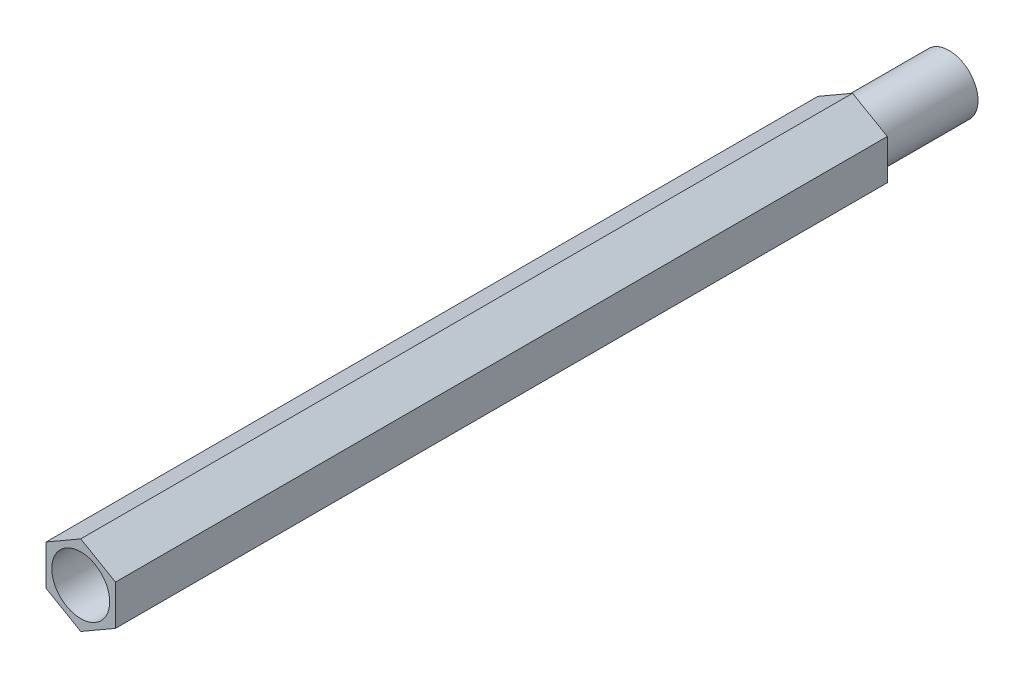
SolidWorks part; units mm, degrees
ref_plane "前视基准面" through (0, 0, 0) normal (0, 0, 1) x (1, 0, 0)
ref_plane "上视基准面" through (0, 0, 0) normal (0, 1, 0) x (1, 0, 0)
ref_plane "右视基准面" through (0, 0, 0) normal (1, 0, 0) x (0, 0, -1)
sketch "草图1" plane through (0, 0, 0) normal (0, 0, 1) x (1, 0, 0)
  line L1 (0, 2.0785) -> (-1.8, 1.0392)
  line L2 (-1.8, 1.0392) -> (-1.8, -1.0392)
  line L3 (-1.8, -1.0392) -> (0, -2.0785)
  line L4 (0, -2.0785) -> (1.8, -1.0392)
  line L5 (1.8, -1.0392) -> (1.8, 1.0392)
  line L6 (1.8, 1.0392) -> (0, 2.0785)
  circle A0 centre (0, 0) radius 1.8 construction
  circle A1 centre (0, 0) radius 1.5
extrude "凸台-拉伸1" add sketch "草图1" along normal blind 40
sketch "草图2" plane through (0, 0, 0) normal (0, 0, -1) x (-1, 0, 0)
  circle A0 centre (0, 0) radius 1.5
extrude "凸台-拉伸2" add sketch "草图2" along normal mid plane 10 contours A0
